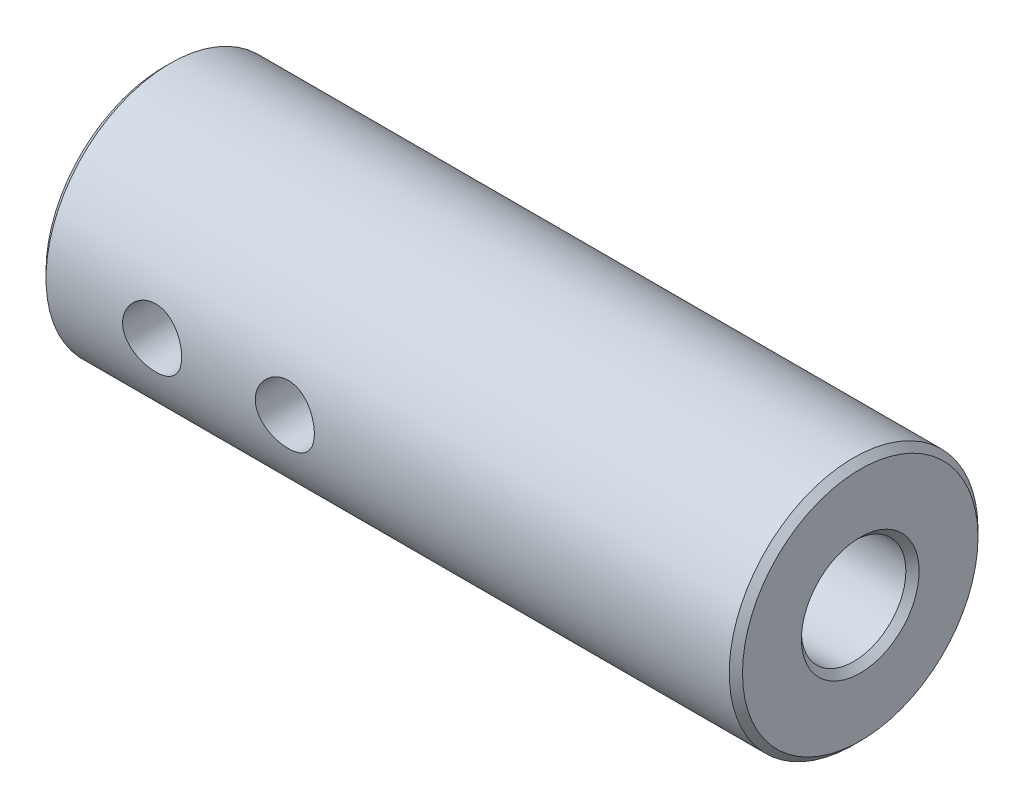
SolidWorks part; units mm, degrees
material "Plain Carbon Steel"
ref_plane "Front Plane" through (0, 0, 0) normal (0, 0, 1) x (1, 0, 0)
ref_plane "Top Plane" through (0, 0, 0) normal (0, 1, 0) x (1, 0, 0)
ref_plane "Right Plane" through (0, 0, 0) normal (1, 0, 0) x (0, 0, -1)
sketch "Sketch1" plane through (0, 0, 0) normal (1, 0, 0) x (0, 0, -1)
  circle A0 centre (0, 0) radius 4.7625
  dimension "D1" = 9.525
extrude "Boss-Extrude1" add sketch "Sketch1" along normal mid plane 26.67
sketch "Sketch2" plane through (13.335, 0, 0) normal (1, 0, 0) x (0, 0, -1)
  circle A0 centre (0, 0) radius 2
  dimension "D1" = 4
extrude "Cut-Extrude1" cut sketch "Sketch2" against normal through all
ref_plane "Plane1" through (0, 0, 4.7625) normal (0, 0, 1) x (1, 0, 0)
hole_wizard "#4-40 Tapped Hole1" positions "Sketch5" profile "Sketch4" tap size "#4-40" standard "Ansi Inch"
sketch "Sketch5" plane through (0, 0, 4.7625) normal (0, 0, 1) x (1, 0, 0)
  line L0 (-13.335, 4.7625) -> (-13.335, -4.7625) construction
  point P1 (-9.017, 0)
  point P3 (-3.937, 0)
  dimension "D1" = 4.318
  dimension "D2" = 5.08
sketch "Sketch4" plane through (-9.017, 0, 4.7625) normal (1, 0, 0) x (0, -1, 0)
  line L0 (0, 0) -> (0, 2.7625)
  line L1 (0, 2.7625) -> (1.1303, 2.7625)
  line L2 (1.1303, 2.7625) -> (1.1303, 0)
  line L5 (1.1303, 0) -> (0, 0)
  line L11 (0, -6.35) -> (0, 107.95) construction
  dimension "Thread Major Dia." = 2.2606
  dimension "Thru Tap Drill Depth" = 2.7625
ref_plane "Plane2" through (0, 0, -4.7625) normal (0, 0, -1) x (-1, 0, 0)
sketch "Sketch7" plane through (0, 0, -4.7625) normal (0, 0, -1) x (-1, 0, 0)
  line L0 (-4.7625, 0) -> (7.9375, 0) construction
  line L1 (-4.7625, 1.1906) -> (7.9375, 1.1906)
  line L2 (-4.7625, -1.1906) -> (7.9375, -1.1906)
  arc A0 (-4.7625, 1.1906) -> (-4.7625, -1.1906) centre (-4.7625, 0) ccw
  arc A1 (7.9375, -1.1906) -> (7.9375, 1.1906) centre (7.9375, 0) ccw
  point P2 (1.5875, 0)
  dimension "D1" = 12.7
  dimension "D2" = 2.3813
  dimension "D3" = 1.5875
extrude "Cut-Extrude2" cut sketch "Sketch7" against normal blind 1.1906
chamfer "Chamfer1" distance 0.254 angle 45 4 edges at (13.335, 0, -4.7625) (-13.335, 0, -4.7625) (13.335, 0, -2) (-13.335, 0, -2)
